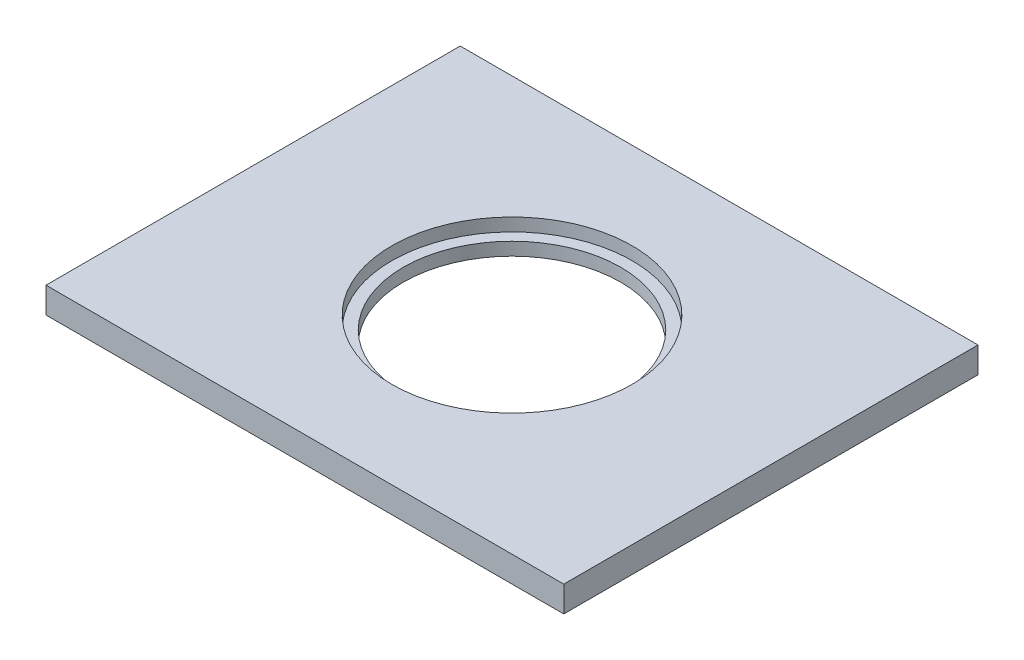
SolidWorks part; units mm, degrees
ref_plane "前视基准面" through (0, 0, 0) normal (0, 0, 1) x (1, 0, 0)
ref_plane "上视基准面" through (0, 0, 0) normal (0, 1, 0) x (1, 0, 0)
ref_plane "右视基准面" through (0, 0, 0) normal (1, 0, 0) x (0, 0, -1)
other "Configuration Table"
sketch "Sketch1" plane through (0, 0, 0) normal (0, 1, 0) x (1, 0, 0)
  line L1 (-50, -40) -> (50, -40)
  line L2 (-50, -40) -> (-50, 40)
  line L3 (-50, 40) -> (50, 40)
  line L4 (50, -40) -> (50, 40)
  line L5 (-50, -40) -> (50, 40) construction
  line L6 (-50, 40) -> (50, -40) construction
  point P0 (0, 0)
  dimension "D1" = 100
  dimension "D2" = 80
extrude "Boss-Extrude1" add sketch "Sketch1" along normal blind 5
sketch "Sketch2" plane through (0, 5, 0) normal (0, 1, 0) x (1, 0, 0)
  circle A0 centre (0, 0) radius 21
  dimension "D1" = 42
extrude "Cut-Extrude1" cut sketch "Sketch2" against normal blind 8
sketch "Sketch3" plane through (0, 5, 0) normal (0, 1, 0) x (1, 0, 0)
  circle A0 centre (0, 0) radius 23.2
  dimension "D1" = 46.4
extrude "Cut-Extrude2" cut sketch "Sketch3" against normal blind 2.5
